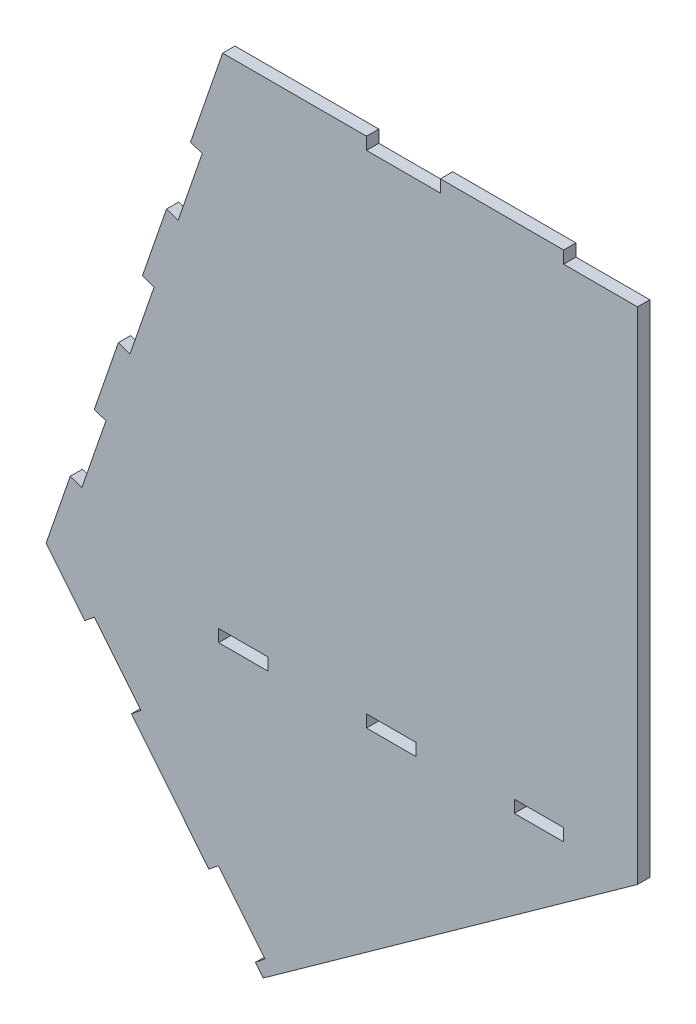
SolidWorks part; units mm, degrees
ref_plane "Front Plane" through (0, 0, 0) normal (0, 0, 1) x (1, 0, 0)
ref_plane "Top Plane" through (0, 0, 0) normal (0, 1, 0) x (1, 0, 0)
ref_plane "Right Plane" through (0, 0, 0) normal (1, 0, 0) x (0, 0, -1)
sketch "Sketch1" plane through (0, 0, 0) normal (0, 0, 1) x (1, 0, 0)
  line L0 (0, 0) -> (152.4, 0) construction
  line L5 (152.4, 0) -> (152.4, 128.9139)
  line L6 (133.35, 132.0889) -> (101.6, 132.0889)
  line L7 (45.4819, 132.0889) -> (37.2124, 108.0728)
  line L8 (0, 0) -> (9.9704, -12.3124)
  line L9 (55.9466, -69.0883) -> (152.4, 0)
  line L10 (95.25, 0) -> (95.25, 3.175)
  line L11 (133.35, 0) -> (120.65, 0)
  line L12 (133.35, 0) -> (133.35, 3.175)
  line L13 (133.35, 3.175) -> (120.65, 3.175)
  line L14 (120.65, 0) -> (120.65, 3.175)
  line L15 (95.25, 0) -> (82.55, 0)
  line L16 (82.55, 0) -> (82.55, 3.175)
  line L17 (95.25, 3.175) -> (82.55, 3.175)
  line L18 (57.15, 0) -> (57.15, 3.175)
  line L19 (57.15, 0) -> (44.45, 0)
  line L20 (44.45, 0) -> (44.45, 3.175)
  line L21 (57.15, 3.175) -> (44.45, 3.175)
  line L22 (133.35, 132.0889) -> (133.35, 128.9139)
  line L23 (133.35, 128.9139) -> (152.4, 128.9139)
  line L24 (101.6, 132.0889) -> (101.6, 128.9139)
  line L25 (101.6, 128.9139) -> (82.55, 128.9139)
  line L26 (82.55, 128.9139) -> (82.55, 132.0889)
  line L27 (82.55, 132.0889) -> (45.4819, 132.0889)
  line L28 (37.2124, 108.0728) -> (40.2145, 107.0391)
  line L29 (40.2145, 107.0391) -> (34.0124, 89.027)
  line L30 (34.0124, 89.027) -> (31.0104, 90.0606)
  line L31 (31.0104, 90.0606) -> (24.8083, 72.0485)
  line L32 (24.8083, 72.0485) -> (27.8103, 71.0148)
  line L33 (27.8103, 71.0148) -> (21.6082, 53.0027)
  line L34 (21.6082, 53.0027) -> (18.6062, 54.0364)
  line L35 (12.4041, 36.0243) -> (15.4062, 34.9906)
  line L36 (15.4062, 34.9906) -> (9.2041, 16.9784)
  line L37 (9.2041, 16.9784) -> (6.2021, 18.0121)
  line L38 (6.2021, 18.0121) -> (0, 0)
  line L39 (18.6062, 54.0364) -> (12.4041, 36.0243)
  line L40 (53.9284, -66.596) -> (56.3958, -64.5979)
  line L41 (56.3958, -64.5979) -> (44.4073, -49.7933)
  line L42 (44.4073, -49.7933) -> (41.9398, -51.7914)
  line L43 (21.9589, -27.117) -> (24.4263, -25.1189)
  line L44 (24.4263, -25.1189) -> (12.4378, -10.3143)
  line L45 (12.4378, -10.3143) -> (9.9704, -12.3124)
  line L46 (21.9589, -27.117) -> (41.9398, -51.7914)
  line L47 (53.9284, -66.596) -> (55.9466, -69.0883)
  dimension "D1" = 71
  dimension "D2" = 152.4
  dimension "D3" = 139.7
  dimension "D4" = 88.9
  dimension "D5" = 51
  dimension "D6" = 12.7
  dimension "D7" = 3.175
  dimension "D8" = 19.05
  dimension "D9" = 3.175
  dimension "D10" = 19.05
  dimension "D11" = 19.05
  dimension "D12" = 3.175
  dimension "D13" = 31.75
  dimension "D14" = 3.175
  dimension "D15" = 19.05
  dimension "D16" = 25.4
  dimension "D17" = 19.05
  dimension "D18" = 3.175
  dimension "D19" = 3.175
  dimension "D20" = 19.05
  dimension "D21" = 19.05
  dimension "D22" = 19.05
  dimension "D23" = 19.05
  dimension "D24" = 19.05
  dimension "D25" = 31.75
  dimension "D26" = 3.175
  dimension "D27" = 3.175
extrude "Boss-Extrude1" add sketch "Sketch1" along normal blind 3.175
